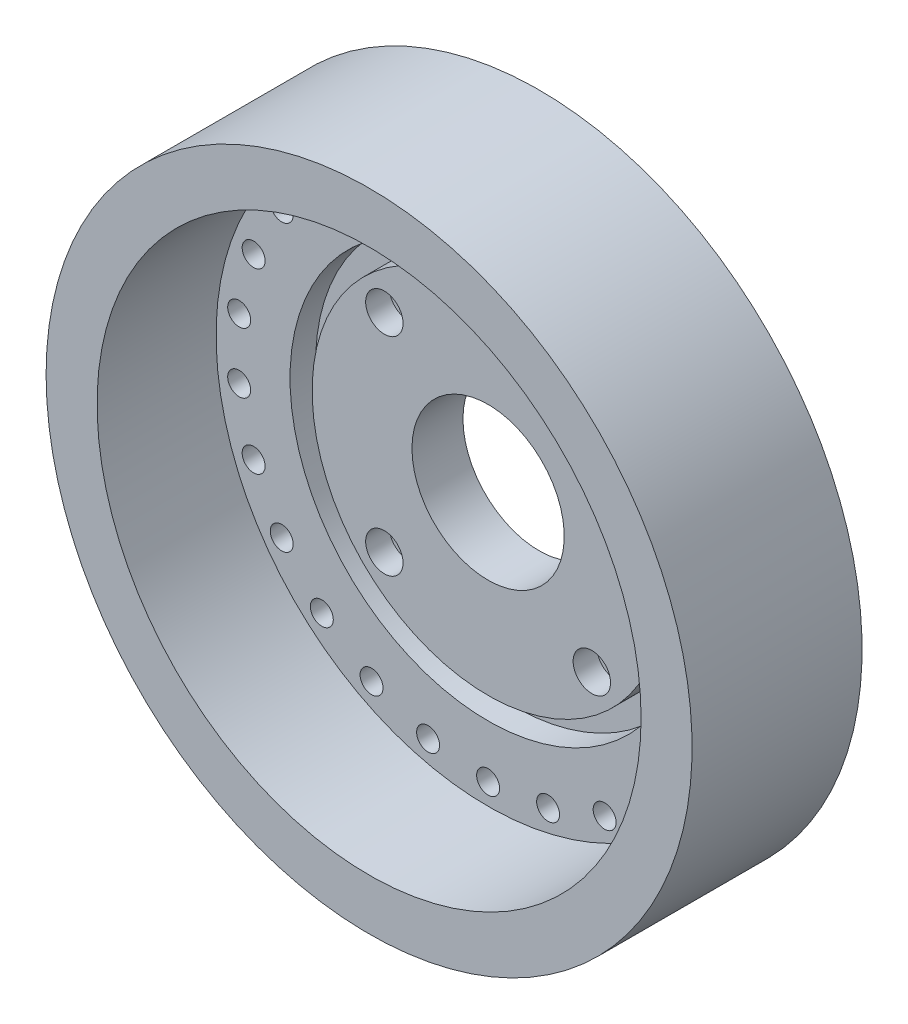
SolidWorks part; units mm, degrees
ref_plane "Front Plane" through (0, 0, 0) normal (0, 0, 1) x (1, 0, 0)
ref_plane "Top Plane" through (0, 0, 0) normal (0, 1, 0) x (1, 0, 0)
ref_plane "Right Plane" through (0, 0, 0) normal (1, 0, 0) x (0, 0, -1)
sketch "Sketch1" plane through (0, 0, 0) normal (0, 0, 1) x (1, 0, 0)
  circle A0 centre (21.15, -21.15) radius 40.64 construction
  circle A1 centre (21.15, -21.15) radius 11.375
  circle A2 centre (21.15, -21.15) radius 48.26
  circle A3 centre (21.15, -21.15) radius 11 construction
  dimension "D1" = 81.28
  dimension "D2" = 22.75
  dimension "D3" = 96.52
extrude "Boss-Extrude1" add sketch "Sketch1" along normal blind 7.62
sketch "Sketch3" plane through (0, 0, 7.62) normal (0, 0, 1) x (1, 0, 0)
  circle A0 centre (21.15, -21.15) radius 37.465 construction
  circle A1 centre (21.15, 16.315) radius 1.7145
  circle A2 centre (30.116, 15.2263) radius 1.7145
  circle A3 centre (38.5609, 12.0236) radius 1.7145
  circle A4 centre (45.9939, 6.893) radius 1.7145
  circle A5 centre (51.9831, 0.1325) radius 1.7145
  circle A6 centre (56.1804, -7.8647) radius 1.7145
  circle A7 centre (58.3418, -16.6341) radius 1.7145
  circle A8 centre (58.3418, -25.6659) radius 1.7145
  circle A9 centre (56.1804, -34.4353) radius 1.7145
  circle A10 centre (51.9831, -42.4325) radius 1.7145
  circle A11 centre (45.9939, -49.193) radius 1.7145
  circle A12 centre (38.5609, -54.3236) radius 1.7145
  circle A13 centre (30.116, -57.5263) radius 1.7145
  circle A14 centre (21.15, -58.615) radius 1.7145
  circle A15 centre (12.184, -57.5263) radius 1.7145
  circle A16 centre (3.7391, -54.3236) radius 1.7145
  circle A17 centre (-3.6939, -49.193) radius 1.7145
  circle A18 centre (-9.6831, -42.4325) radius 1.7145
  circle A19 centre (-13.8804, -34.4353) radius 1.7145
  circle A20 centre (-16.0418, -25.6659) radius 1.7145
  circle A21 centre (-16.0418, -16.6341) radius 1.7145
  circle A22 centre (-13.8804, -7.8647) radius 1.7145
  circle A23 centre (-9.6831, 0.1325) radius 1.7145
  circle A24 centre (-3.6939, 6.893) radius 1.7145
  circle A25 centre (3.7391, 12.0236) radius 1.7145
  circle A26 centre (12.184, 15.2263) radius 1.7145
  dimension "D1" = 74.93
  dimension "D2" = 3.429
  dimension "D3" = 26
extrude "Cut-Extrude1" cut sketch "Sketch3" against normal blind 3.81
sketch "Sketch5" plane through (0, 0, 7.62) normal (0, 0, 1) x (1, 0, 0)
  circle A0 centre (21.15, -21.15) radius 48.26
  circle A1 centre (21.15, -21.15) radius 40.64
  circle A2 centre (21.15, -21.15) radius 48.26 construction
  arc A3 (18.9997, -19.8747) -> (21.7722, -18.7287) centre (21.15, -21.15) ccw construction
  dimension "D2" = 81.28
extrude "Boss-Extrude2" add sketch "Sketch5" along normal blind 17.78
sketch "Sketch8" plane through (0, 0, 25.4) normal (0, 0, 1) x (1, 0, 0)
  line L0 (-19.4873, -21.6141) -> (-27.1078, -21.6141) construction
  line L1 (21.6141, -61.7873) -> (21.6141, -69.4078) construction
  line L2 (61.7873, -20.6859) -> (69.4078, -20.6859) construction
  line L3 (20.6859, 19.4873) -> (20.6859, 27.1078) construction
  circle A0 centre (21.15, -21.15) radius 44.45 construction
  circle A2 centre (20.6859, 23.2976) radius 2
  circle A3 centre (-23.2976, -21.6141) radius 2
  circle A4 centre (21.6141, -65.5976) radius 2
  circle A5 centre (65.5976, -20.6859) radius 2
  arc A11 (-23.2536, -25.4674) -> (-23.3406, -17.8479) centre (-23.2971, -21.6576) ccw construction
  circle A12 centre (21.15, -21.15) radius 48.26 construction
  arc A13 (25.4674, -65.5536) -> (17.8479, -65.6406) centre (21.6576, -65.5971) ccw construction
  arc A14 (65.5536, -16.8326) -> (65.6406, -24.4521) centre (65.5971, -20.6424) ccw construction
  arc A15 (16.8326, 23.2536) -> (24.4521, 23.3406) centre (20.6424, 23.2971) ccw construction
  dimension "D1" = 88.9
  dimension "D2" = 4
sketch "Sketch9" plane through (0, 0, 7.62) normal (0, 0, 1) x (1, 0, 0)
  line L0 (5.65, -5.65) -> (36.65, -5.65) construction
  circle A0 centre (21.15, -21.15) radius 21.9203 construction
  circle A1 centre (5.65, -5.65) radius 2 construction
  circle A2 centre (5.65, -5.65) radius 2.794 construction
  circle A3 centre (36.65, -5.65) radius 2.794 construction
  circle A4 centre (36.65, -5.65) radius 2 construction
  circle A5 centre (36.65, -36.65) radius 2.794 construction
  circle A6 centre (36.65, -36.65) radius 2 construction
  circle A7 centre (5.65, -36.65) radius 2.794 construction
  circle A8 centre (5.65, -36.65) radius 2 construction
  circle A9 centre (21.15, -21.15) radius 48.26 construction
  dimension "D1" = 5.588
  dimension "D2" = 4
  dimension "D4" = 43.8406
  dimension "D3" = 4
sketch "Sketch10" plane through (0, 0, 7.62) normal (0, 0, 1) x (1, 0, 0)
  circle A0 centre (36.65, -36.65) radius 2.794 construction
  circle A1 centre (5.65, -36.65) radius 2.794 construction
  circle A2 centre (5.65, -5.65) radius 2.794 construction
  circle A3 centre (36.65, -5.65) radius 2.794 construction
  circle A4 centre (36.65, -36.65) radius 2.794
  circle A5 centre (5.65, -36.65) radius 2.794
  circle A6 centre (5.65, -5.65) radius 2.794
  circle A7 centre (36.65, -5.65) radius 2.794
extrude "Cut-Extrude2" cut sketch "Sketch10" against normal blind 3.556
sketch "Sketch11" plane through (0, 0, 7.62) normal (0, 0, 1) x (1, 0, 0)
  circle A0 centre (36.65, -36.65) radius 2 construction
  circle A1 centre (5.65, -36.65) radius 2 construction
  circle A2 centre (36.65, -5.65) radius 2 construction
  circle A3 centre (5.65, -5.65) radius 2 construction
  circle A4 centre (36.65, -36.65) radius 2
  circle A5 centre (5.65, -36.65) radius 2
  circle A6 centre (36.65, -5.65) radius 2
  circle A7 centre (5.65, -5.65) radius 2
extrude "Cut-Extrude3" cut sketch "Sketch11" against normal through all
sketch "Sketch13" plane through (0, 0, 7.62) normal (0, 0, -1) x (-1, 0, 0)
  circle A0 centre (-21.15, -21.15) radius 27.94 construction
  circle A1 centre (-21.15, -21.15) radius 29.591
  circle A2 centre (-21.15, -21.15) radius 26.289
  dimension "D1" = 55.88
  dimension "D2" = 1.651
  dimension "D3" = 1.651
extrude "Cut-Extrude7" cut sketch "Sketch13" along normal blind 3.81 contours A1 A2
